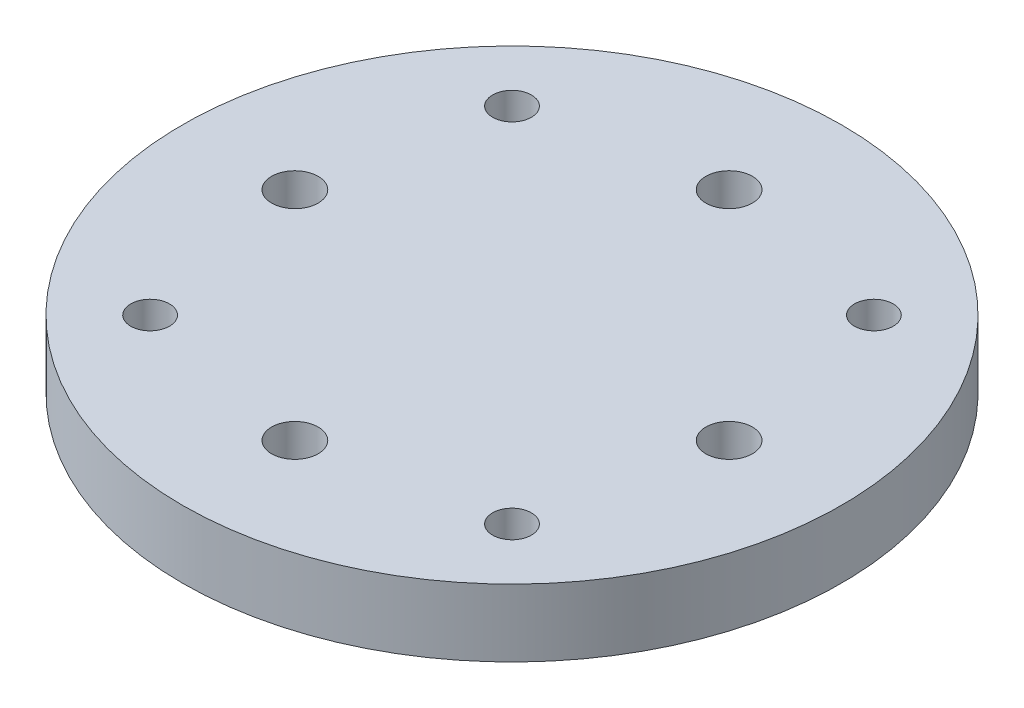
SolidWorks part; units mm, degrees
ref_plane "Спереди" through (0, 0, 0) normal (0, 0, 1) x (1, 0, 0)
ref_plane "Сверху" through (0, 0, 0) normal (0, 1, 0) x (1, 0, 0)
ref_plane "Справа" through (0, 0, 0) normal (1, 0, 0) x (0, 0, -1)
sketch "Эскиз1" plane through (0, 0, 0) normal (0, 1, 0) x (1, 0, 0)
  circle A0 centre (0, 0) radius 42.5
extrude "Вытянуть1" add sketch "Эскиз1" along normal blind 8.7
sketch "Эскиз2" plane through (0, 8.7, 0) normal (0, 1, 0) x (1, 0, 0)
  line L0 (0, 0) -> (0, -50.1277) construction
  line L1 (0, 0) -> (-57.9434, 0) construction
  line L2 (1.6169, -1.6169) -> (-44.3567, 44.3567) construction
  circle A0 centre (0, 28) radius 3
  circle A1 centre (28, 0) radius 3
  circle A2 centre (0, -28) radius 3
  circle A3 centre (-28, 0) radius 3
  circle A4 centre (-23.3345, 23.3345) radius 2.5
  circle A5 centre (23.3345, 23.3345) radius 2.5
  circle A6 centre (23.3345, -23.3345) radius 2.5
  circle A7 centre (-23.3345, -23.3345) radius 2.5
  dimension "D1" = 28
  dimension "D3" = 33
  dimension "D2" = 45
extrude "Вытянуть2" cut sketch "Эскиз2" against normal blind 8.7
